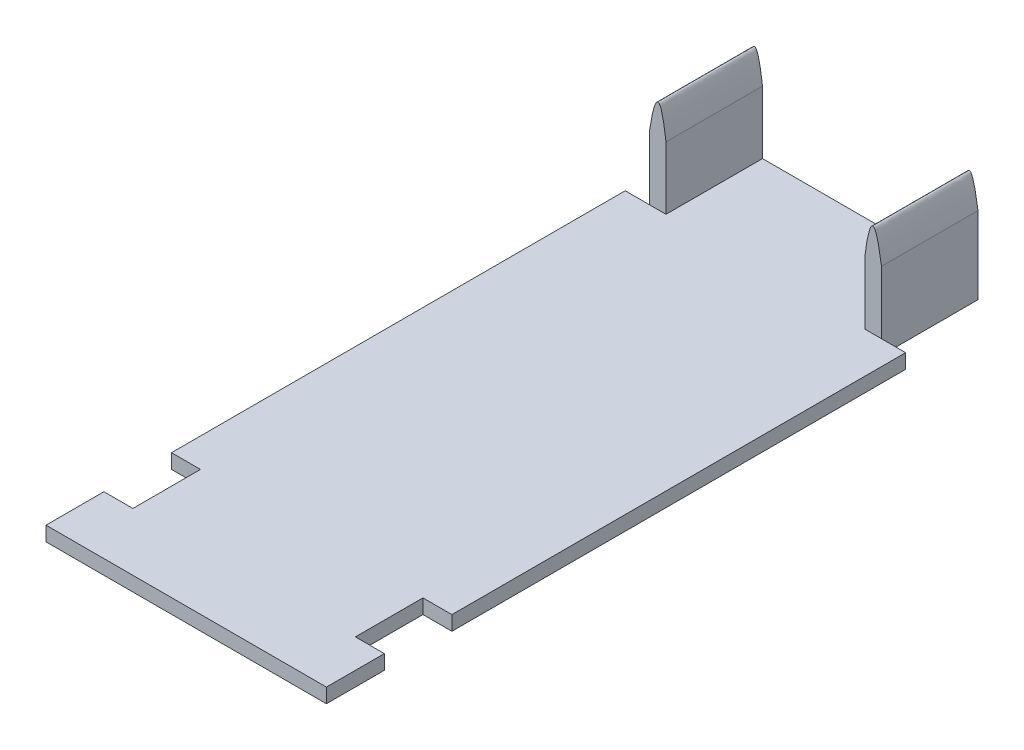
SolidWorks part; units mm, degrees
ref_plane "Front Plane" through (0, 0, 0) normal (0, 0, 1) x (1, 0, 0)
ref_plane "Top Plane" through (0, 0, 0) normal (0, 1, 0) x (1, 0, 0)
ref_plane "Right Plane" through (0, 0, 0) normal (1, 0, 0) x (0, 0, -1)
sketch "Sketch1" plane through (0, 0, 0) normal (0, 0, 1) x (1, 0, 0)
  line L0 (-31.0002, 89.8) -> (31.0002, 89.8) construction
  line L1 (-19.45, 0) -> (-19.45, 22.2)
  line L2 (-19.45, 22.2) -> (19.45, 22.2) construction
  line L3 (19.45, 3) -> (19.45, 22.2)
  line L4 (19.45, 22.2) -> (25.05, 22.2) construction
  line L5 (22.25, 22.2) -> (22.25, 16.6) construction
  line L6 (25.05, 22.2) -> (25.05, 71.1)
  line L7 (29, 72.2) -> (29, -3)
  line L8 (22.25, 16.6) -> (22.25, 71.1) construction
  line L9 (19.6329, 71.1) -> (19.6329, 64.8)
  line L10 (-22.25, 16.6) -> (-22.25, 71.1) construction
  line L11 (-22.25, 22.2) -> (-22.25, 16.6) construction
  line L12 (-19.45, 22.2) -> (-25.05, 22.2) construction
  line L13 (-19.6329, 71.1) -> (-19.5947, 64.8)
  line L14 (-29, 72.2) -> (-29, 0)
  line L15 (-25.05, 22.2) -> (-25.05, 71.1)
  line L16 (-19.45, 0) -> (-19.45, 22.2)
  line L17 (-24.05, 64.8) -> (-24.05, 48.8)
  line L18 (0, 89.8) -> (0, 69.3) construction
  line L19 (25.05, 64.8) -> (33.55, 64.8)
  line L20 (-25.05, 64.8) -> (-33.55, 64.8)
  line L21 (33.55, 64.8) -> (33.55, 61.8)
  line L22 (33.55, 61.8) -> (29, 61.8)
  line L23 (-30.35, 3) -> (29, 3)
  line L24 (-33.55, 0) -> (33.55, 0)
  line L25 (-33.55, 0) -> (-33.55, 11.2)
  line L26 (-33.55, 11.2) -> (-29, 11.2)
  line L27 (33.55, 11.2) -> (29, 11.2)
  line L28 (33.55, 0) -> (33.55, 11.2)
  line L29 (-33.55, 64.8) -> (-33.55, 61.8)
  line L30 (-33.55, 61.8) -> (-29, 61.8)
  line L31 (-24.05, 48.8) -> (24.05, 48.8)
  line L32 (-20.5947, 64.8) -> (-20.5947, 51.8)
  line L33 (-20.5947, 51.8) -> (20.5947, 51.8)
  line L34 (24.05, 64.8) -> (24.05, 48.8)
  line L35 (20.5947, 64.8) -> (20.5947, 51.8)
  arc A0 (-19.45, 22.2) -> (19.45, 22.2) centre (0, 51.8) ccw
  arc A1 (-19.5947, 64.8) -> (19.6329, 64.8) centre (0.0191, 24.3054) cw
  arc A2 (-33.55, 64.8) -> (33.55, 64.8) centre (0, 54.7879) cw
  spline S0 degree 2 poles (19.45, 22.2) (22.25, 11) (25.05, 22.2) knots 0 0 0 1 1 1
  spline S1 degree 2 poles (19.6329, 64.8) (22.1871, 77.4003) (25.05, 64.8) knots 0 0 0 1 1 1
  spline S2 degree 2 poles (-19.5947, 64.8) (-22.2005, 77.4002) (-25.05, 64.8) knots 0 0 0 1 1 1
  spline S3 degree 2 poles (-19.45, 22.2) (-22.25, 11) (-25.05, 22.2) knots 0 0 0 1 1 1
  spline S4 degree 2 poles (-25.05, 64.8) (-22.2005, 77.4002) (-19.5947, 64.8) knots 0 0 0 1 1 1
  spline S5 degree 2 poles (-24.05, 64.8) (-22.1878, 77.4001) (-20.5947, 64.8) knots 0 0 0 1 1 1
  spline S6 degree 2 poles (24.05, 64.8) (22.1878, 77.4001) (20.5947, 64.8) knots 0 0 0 1 1 1
  point P8 (0, 22.2)
  point P37 (0, 89.8)
  point P47 (-0.675, 3)
  point P50 (0, 0)
  point P56 (0, 89.8)
  point P63 (0, 48.8)
  dimension "D12" = 1
  dimension "D2" = 22.2
  dimension "D3" = 38.9
  dimension "D4" = 5.6
  dimension "D5" = 5.6
  dimension "D6" = 5.4171
  dimension "D7" = 29
  dimension "D8" = 29
  dimension "D9" = 6.3
  dimension "D10" = 0
  dimension "D11" = 6.3
  dimension "D13" = 20.5
  dimension "D14" = 8.5
  dimension "D15" = 8.5
  dimension "D16" = 89.8
  dimension "D17" = 3
  dimension "D18" = 11.2
  dimension "D19" = 3
  dimension "D20" = 1
  dimension "D21" = 13
extrude "Boss-Extrude1" add sketch "Sketch1" along normal blind 20 contours L31 L34 S6 L35 L33 L32 S5 L17
sketch "Sketch2" plane through (0, 0, 20) normal (0, 0, 1) x (1, 0, 0)
  line L0 (24.05, 64.8) -> (24.05, 48.8) construction
  line L1 (-29.05, 48.8) -> (29.05, 48.8)
  line L2 (-29.05, 48.8) -> (-29.05, 51.8)
  line L3 (-29.05, 51.8) -> (29.05, 51.8)
  line L4 (29.05, 48.8) -> (29.05, 51.8)
  line L5 (-24.05, 64.8) -> (-24.05, 48.8) construction
  line L6 (-24.05, 48.8) -> (24.05, 48.8) construction
  line L7 (-24.05, 48.8) -> (24.05, 48.8)
  point P10 (0, 48.8)
  line M6 (-24.05, 64.8) -> (-24.05, 48.8)
  line M7 (-24.05, 48.8) -> (24.05, 48.8)
  line M8 (24.05, 48.8) -> (24.05, 64.8)
  line M11 (20.5947, 51.8) -> (-20.5947, 51.8)
  dimension "D1" = 3
  dimension "D2" = 5
  dimension "D3" = 5
extrude "Boss-Extrude2" add sketch "Sketch2" along normal blind 120 contours L3 L2 L1 M6 | L3 M6 M7 M8 M11 | L1 L4 L3 M8
sketch "Sketch3" plane through (0, 0, 140) normal (0, 0, 1) x (1, 0, 0)
  line L0 (-29.05, 51.8) -> (29.05, 51.8) construction
  line L1 (-24.9, 51.8) -> (24.9, 51.8)
  line L2 (-24.9, 51.8) -> (-24.9, 48.8)
  line L3 (-24.9, 48.8) -> (24.9, 48.8)
  line L4 (24.9, 51.8) -> (24.9, 48.8)
  line L5 (-29.05, 48.8) -> (29.05, 48.8) construction
  line L6 (-29.05, 51.8) -> (29.05, 51.8)
  line L7 (-29.05, 48.8) -> (29.05, 48.8)
  line L8 (0, 51.8) -> (0, 48.8)
  point P12 (0, 48.8)
  dimension "D1" = 24.9
sketch "Sketch4" plane through (0, 51.8, 0) normal (0, 1, 0) x (1, 0, 0)
  line L0 (0, 0) -> (0, -140)
  line L1 (-29.05, -114) -> (-23.05, -114)
  line L2 (-29.05, -114) -> (-29.05, -128)
  line L3 (-29.05, -128) -> (-23.05, -128)
  line L4 (-23.05, -114) -> (-23.05, -128)
  line L5 (29.05, -128) -> (23.05, -128)
  line L6 (23.05, -114) -> (23.05, -128)
  line L7 (29.05, -114) -> (23.05, -114)
  line L8 (29.05, -114) -> (29.05, -128)
  line L10 (20.5947, 0) -> (-20.5947, 0)
  line L11 (-20.5947, 0) -> (-20.5947, -20)
  line L12 (-20.5947, -20) -> (-24.05, -20)
  line L13 (-24.05, -20) -> (-29.05, -20)
  line L14 (-29.05, -20) -> (-29.05, -140)
  line L15 (-29.05, -140) -> (29.05, -140)
  line L16 (29.05, -140) -> (29.05, -20)
  line L17 (29.05, -20) -> (24.05, -20)
  line L18 (24.05, -20) -> (20.5947, -20)
  line L19 (20.5947, -20) -> (20.5947, 0)
  line L20 (20.5947, 0) -> (-20.5947, 0)
  line L21 (-20.5947, 0) -> (-20.5947, -20)
  line L22 (-20.5947, -20) -> (-24.05, -20)
  line L23 (-24.05, -20) -> (-29.05, -20)
  line L24 (-29.05, -20) -> (-29.05, -140)
  line L25 (-29.05, -140) -> (29.05, -140)
  line L26 (29.05, -140) -> (29.05, -20)
  line L27 (29.05, -20) -> (24.05, -20)
  line L28 (24.05, -20) -> (20.5947, -20)
  line L29 (20.5947, -20) -> (20.5947, 0)
  line M20 (-29.05, -20) -> (-29.05, -140)
  line M22 (29.05, -140) -> (29.05, -20)
  dimension "D2" = 6
  dimension "D3" = 14
  dimension "D4" = 12
  dimension "D1" = 0
extrude "Cut-Extrude1" cut sketch "Sketch4" against normal blind 10 contours L4 L1 L3 M20 | L7 L6 L5 M22
